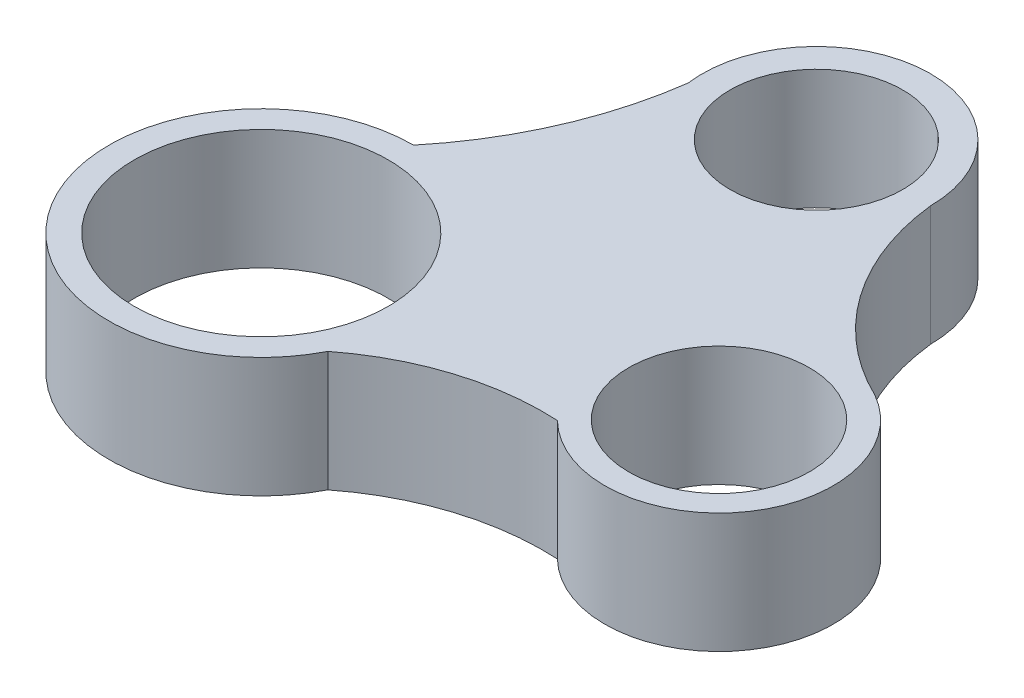
SolidWorks part; units mm, degrees
ref_plane "Front Plane" through (0, 0, 0) normal (0, 0, 1) x (1, 0, 0)
ref_plane "Top Plane" through (0, 0, 0) normal (0, 1, 0) x (1, 0, 0)
ref_plane "Right Plane" through (0, 0, 0) normal (1, 0, 0) x (0, 0, -1)
sketch "Sketch1" plane through (0, 0, 0) normal (0, 1, 0) x (1, 0, 0)
  circle A0 centre (0, 0) radius 12.7
  circle A1 centre (16.4008, 29.8792) radius 9.525
  circle A2 centre (32.56, 5.6018) radius 9.525
  arc A3 (6.9594, 28.6203) -> (0, 12.7) centre (-24.4218, 32.857) cw
  arc A4 (25.9258, 29.8792) -> (37.2857, 13.8718) centre (46.0415, 32.12) ccw
  arc A5 (11.3158, -5.7657) -> (25.8772, -1.1854) centre (24.6947, -22.8627) cw
  circle A6 centre (16.4008, 29.8792) radius 7.1995
  circle A7 centre (0, 0) radius 10.5879
  circle A8 centre (32.56, 5.6018) radius 7.5318
  dimension "D1" = 19.05
  dimension "D2" = 25.4
  dimension "D3" = 19.05
extrude "Boss-Extrude1" add sketch "Sketch1" along normal blind 10 contours A0 A5 A2 A4 A1 A3 | A0 A7 | A1 A6 | A4 A2 A8
